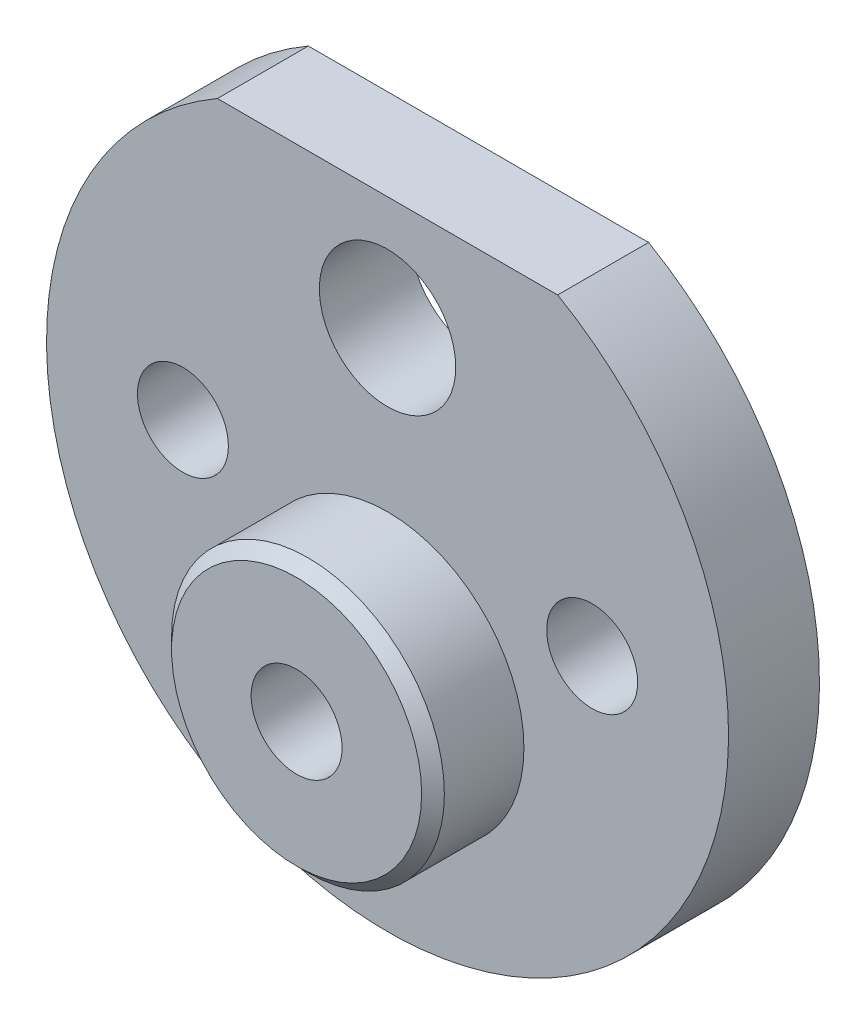
SolidWorks part; units mm, degrees
ref_plane "Front Plane" through (0, 0, 0) normal (0, 0, 1) x (1, 0, 0)
ref_plane "Top Plane" through (0, 0, 0) normal (0, 1, 0) x (1, 0, 0)
ref_plane "Right Plane" through (0, 0, 0) normal (1, 0, 0) x (0, 0, -1)
sketch "Sketch1" plane through (0, 0, 0) normal (0, 0, 1) x (1, 0, 0)
  line L0 (-7.4833, 13) -> (7.4833, 13)
  line L1 (0, 0) -> (0, 11.3972) construction
  line L2 (0, 0) -> (-11.7545, 0) construction
  arc A0 (-7.4833, 13) -> (7.4833, 13) centre (0, 0) ccw
  circle A1 centre (-9, 0) radius 2
  circle A2 centre (0, 8) radius 3
  circle A3 centre (9, 0) radius 2
  point P12 (0, 0)
  dimension "D1" = 30
  dimension "D3" = 6
  dimension "D5" = 4
  dimension "D8" = 4
  dimension "D2" = 13
  dimension "D4" = 8
  dimension "D6" = 9
  dimension "D7" = 9
extrude "Boss-Extrude1" add sketch "Sketch1" along normal blind 4
sketch "Sketch2" plane through (0, 0, 4) normal (0, 0, 1) x (1, 0, 0)
  circle A0 centre (0, -5) radius 6
  dimension "D2" = 12
  dimension "D1" = 5
extrude "Boss-Extrude2" add sketch "Sketch2" along normal blind 4
sketch "Sketch3" plane through (0, 0, 8) normal (0, 0, 1) x (1, 0, 0)
  circle A0 centre (0, -5) radius 2
  dimension "D1" = 4
extrude "Cut-Extrude1" cut sketch "Sketch3" against normal through all
chamfer "Chamfer1" distance 0.5 angle 45 1 edges at (6, -5, 8)
